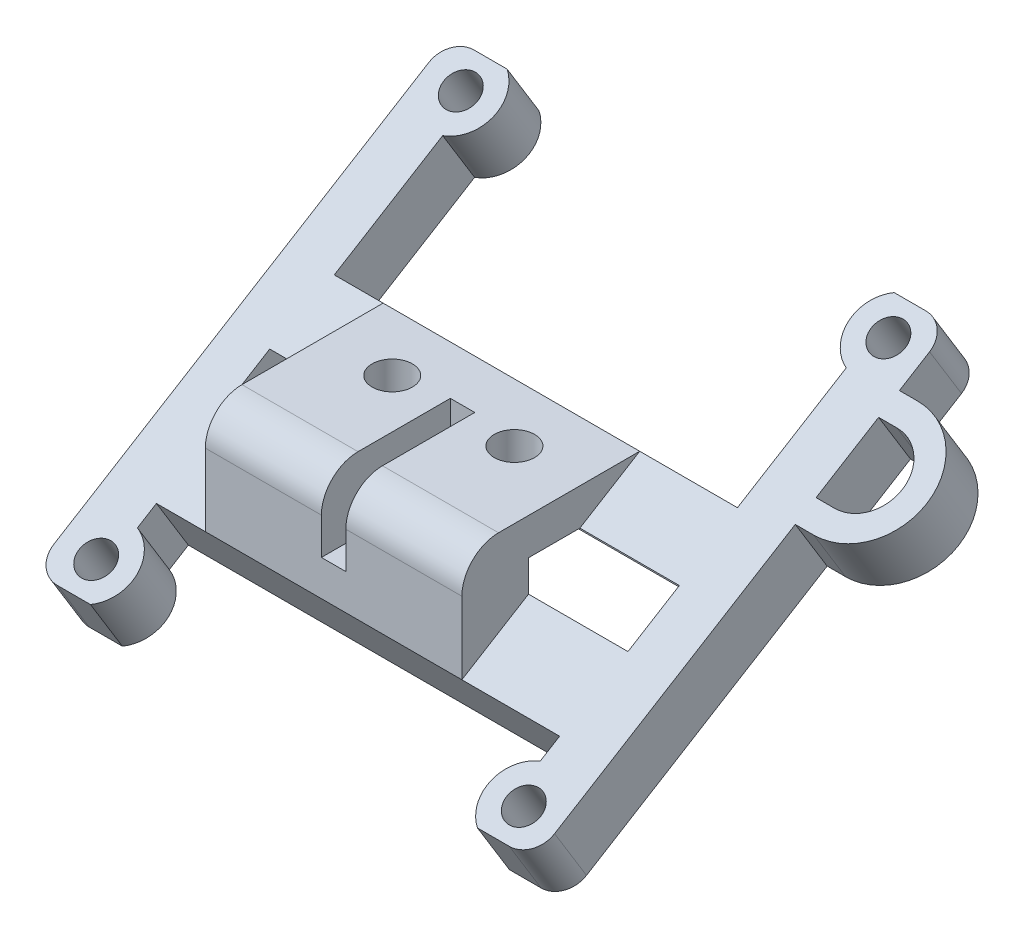
SolidWorks part; units mm, degrees
ref_plane "前视基准面" through (0, 0, 0) normal (0, 0, 1) x (1, 0, 0)
ref_plane "上视基准面" through (0, 0, 0) normal (0, 1, 0) x (1, 0, 0)
ref_plane "右视基准面" through (0, 0, 0) normal (1, 0, 0) x (0, 0, -1)
sketch "草图1" plane through (0, 0, 0) normal (0, 1, 0) x (1, 0, 0)
  line L1 (0, 0) -> (28, 0)
  line L2 (0, 0) -> (0, 15)
  line L3 (0, 15) -> (28, 15)
  line L4 (28, 0) -> (28, 15)
  dimension "D1" = 15
  dimension "D2" = 28
extrude "凸台-拉伸1" add sketch "草图1" along normal blind 5
sketch "草图2" plane through (0, 0, 0) normal (-1, 0, 0) x (0, 0, 1)
  line L0 (4.8114, -9.8007) -> (-29.2942, 11.0992)
  line L1 (-29.2942, 11.0992) -> (-27.988, 13.2308)
  line L2 (4.8114, -9.8007) -> (6.1176, -7.6691)
  line L3 (-27.988, 13.2308) -> (-14.5565, 5)
  line L4 (0, 0) -> (0, -3.9202)
  line L5 (-15, 0) -> (0, 0) construction
  line L6 (0, 5) -> (0, 0) construction
  line L8 (0, -3.9202) -> (6.1176, -7.6691)
  line L9 (0, 0) -> (0, 5)
  line L10 (0, 5) -> (-14.5565, 5)
  dimension "D1" = 2.5
  dimension "D2" = 2.5
extrude "凸台-拉伸2" add sketch "草图2" along normal blind 13 and the other way up to surface other way up to face at (28, 2.5, -7.5)
sketch "草图3" plane through (-13, 0, 0) normal (-1, 0, 0) x (0, 0, 1)
  line L3 (-15, 0) -> (-11.1819, 0)
  line L4 (-11.1819, 0) -> (-15, 2.3397)
  line L5 (-15, 2.3397) -> (-15, 0)
  line L6 (-15, 0) -> (-11.1819, 0)
  line L7 (-11.1819, 0) -> (-15, 2.3397)
  line L8 (-15, 2.3397) -> (-15, 0)
  dimension "D1" = 0
extrude "切除-拉伸1" cut sketch "草图3" against normal through all
sketch "草图8" plane through (0, -4.9816, -3.0527) normal (0, -0.8526, -0.5225) x (1, 0, 0)
  line L4 (28, 9.2233) -> (-13, 9.2233)
  line L5 (-13, 9.2233) -> (-13, -30.7767)
  line L6 (-13, -30.7767) -> (28, -30.7767)
  line L7 (28, -30.7767) -> (28, 9.2233)
  line L8 (28, 9.2233) -> (-13, 9.2233)
  line L9 (-13, 9.2233) -> (-13, -30.7767)
  line L10 (-13, -30.7767) -> (28, -30.7767)
  line L11 (28, -30.7767) -> (28, 9.2233)
  dimension "D1" = 0
extrude "凸台-拉伸3" add sketch "草图8" along normal blind 2.5
sketch "草图4" plane through (0, -7.1132, -4.359) normal (0, -0.8526, -0.5225) x (1, 0, 0)
  circle A0 centre (-9.9452, 6.7233) radius 1.4
  circle A1 centre (25.0548, 6.7233) radius 1.4
  circle A2 centre (25.0548, -28.2767) radius 1.4
  circle A3 centre (-9.9452, -28.2767) radius 1.4
  dimension "D1" = 2.8
  dimension "D2" = 2.8
  dimension "D3" = 2.8
  dimension "D4" = 2.8
extrude "切除-拉伸2" cut sketch "草图4" against normal blind 7
sketch "草图5" plane through (0, 5, 0) normal (0, 1, 0) x (1, 0, 0)
  line L0 (0.5, 9.8) -> (10.5, 9.8) construction
  line L1 (-13, -3.5052) -> (-13, 30.6005) construction
  circle A0 centre (10.5, 9.8) radius 1.65
  circle A1 centre (0.5, 9.8) radius 1.65
  dimension "D1" = 3.3
  dimension "D2" = 3.3
  dimension "D3" = 13.5
  dimension "D4" = 10
extrude "切除-拉伸3" cut sketch "草图5" against normal through all
ref_plane "基准面1" through (0, 2, 0) normal (0, 1, 0) x (1, 0, 0)
sketch "草图6" plane through (0, 2, 0) normal (0, 1, 0) x (1, 0, 0)
  line L1 (-9.391, 13.2275) -> (24.1407, 13.2275)
  line L2 (-9.391, 13.2275) -> (-9.391, 5.454)
  line L3 (-9.391, 5.454) -> (24.1407, 5.454)
  line L4 (24.1407, 13.2275) -> (24.1407, 5.454)
  circle A0 centre (0.5, 9.8) radius 3.1 construction
  circle A1 centre (10.5, 9.8) radius 3.1 construction
  dimension "D1" = 6.2
  dimension "D2" = 6.2
extrude "切除-拉伸4" cut sketch "草图6" against normal blind 11
fillet "圆角1" radius 2 4 edges at (-13, -9.8007, 4.8114) (28, -9.8007, 4.8114) (28, 11.0992, -29.2942) (-13, 11.0992, -29.2942)
sketch "草图9" plane through (0, -2.85, -1.7465) normal (0, 0.8526, 0.5225) x (1, 0, 0)
  line L3 (28, -2.0483) -> (-13, -2.0483) construction
  line L4 (26, -9.2233) -> (-11, -9.2233) construction
  line L5 (-8.2869, -9.2233) -> (23.3965, -9.2233)
  line L6 (-9, -3.8761) -> (-9, -2.0483)
  line L7 (-9, -2.0483) -> (24, -2.0483)
  line L8 (-9, 19.0239) -> (-9, 15.0239)
  line L9 (28, 15.0239) -> (-13, 15.0239) construction
  line L10 (-9, 15.0239) -> (24, 15.0239)
  line L11 (24, 15.0239) -> (24, 19.0239)
  line L12 (-11, 30.7767) -> (26, 30.7767) construction
  line L16 (24, 19.0239) -> (24, 25.4683)
  line L17 (23.3965, 30.7767) -> (-8.2869, 30.7767)
  line L18 (-9, 25.4295) -> (-9, 19.0239)
  line L19 (24, -3.9148) -> (24, -2.0483)
  arc A0 (23.3965, 30.7767) -> (24, 25.4683) centre (25.0548, 28.2767) ccw
  arc A1 (-9, 25.4295) -> (-8.2869, 30.7767) centre (-9.9452, 28.2767) ccw
  arc A4 (-8.2869, -9.2233) -> (-9, -3.8761) centre (-9.9452, -6.7233) ccw
  arc A5 (24, -3.9148) -> (23.3965, -9.2233) centre (25.0548, -6.7233) ccw
  dimension "D2" = 6
  dimension "D3" = 6
  dimension "D4" = 6
  dimension "D5" = 6
extrude "切除-拉伸5" cut sketch "草图9" against normal through all
sketch "草图10" plane through (0, 5, 0) normal (0, 1, 0) x (1, 0, 0)
  line L0 (19.9278, 10.5565) -> (19.9278, -1) construction
  line L2 (6.5011, 10.5565) -> (6.5011, -1)
  line L4 (4.5011, 10.5565) -> (4.5011, -1)
  line L5 (0.0722, 10.5565) -> (0.0722, -1) construction
  line L6 (6.5011, 10.5565) -> (4.5011, 10.5565)
  line L7 (0.0722, 10.5565) -> (-9, 10.5565) construction
  line L8 (4.5011, -1) -> (6.5011, -1)
  line L9 (19.9278, -1) -> (24, -1) construction
  line L10 (19.9278, -1) -> (6.5011, -1) construction
  line L11 (4.5011, -1) -> (0.0722, -1) construction
  line L12 (-13, 0) -> (28, 0) construction
  line L13 (19.9278, 10.5565) -> (6.5011, 10.5565) construction
  line L14 (4.5011, 10.5565) -> (0.0722, 10.5565) construction
  line L15 (-9, 14.5565) -> (24, 14.5565) construction
  line L16 (24, -1) -> (24, 10.5565) construction
  line L17 (24, 10.5565) -> (19.9278, 10.5565) construction
  line L18 (-9, 10.5565) -> (-9, -1) construction
  line L19 (-9, -1) -> (0.0722, -1) construction
  dimension "D2" = 4
  dimension "D3" = 2
  dimension "D1" = 1
extrude "切除-拉伸6" cut sketch "草图10" against normal blind 6
sketch "草图11" plane through (-13, 0, 0) normal (-1, 0, 0) x (0, 0, 1)
  line L0 (0, -3.9202) -> (-14.5565, 5)
  line L1 (4.4124, -6.6241) -> (0, -3.9202) construction
  line L2 (0, 5) -> (-14.5565, 5) construction
  line L3 (-14.5565, 5) -> (-26.2827, 12.1858) construction
  line L4 (-14.5565, 5) -> (0, 5)
  line L5 (0, -3.9202) -> (0, 5) construction
  line L6 (0, 5) -> (0, -3.9202)
extrude "切除-拉伸8" cut sketch "草图11" against normal blind 8
sketch "草图12" plane through (28, 0, 0) normal (1, 0, 0) x (0, 0, -1)
  line L0 (14.5565, 5) -> (0, -3.9202)
  line L1 (0, -3.9202) -> (0, 5)
  line L2 (0, 5) -> (14.5565, 5)
extrude "切除-拉伸9" cut sketch "草图12" against normal blind 12
fillet "圆角2" radius 3 2 edges at (11.2505, 5, 0) (-0.2495, 5, 0)
sketch "草图13" plane through (0, -7.1132, -4.359) normal (0, -0.8526, -0.5225) x (1, 0, 0)
  line L0 (24.8936, -20.8821) -> (29.5126, -20.8821) construction
  line L1 (27.2031, -17.8821) -> (29.5126, -17.8821)
  line L2 (27.2031, -23.8821) -> (29.5126, -23.8821)
  line L3 (27.2031, -15.8821) -> (29.5126, -15.8821)
  line L4 (27.2031, -25.8821) -> (29.5126, -25.8821)
  line L5 (27.2031, -15.8821) -> (27.2031, -17.8821)
  line L6 (27.2031, -23.8821) -> (27.2031, -25.8821)
  line L7 (24.8936, -25.8821) -> (29.5126, -25.8821) construction
  line L8 (24.8936, -23.8821) -> (29.5126, -23.8821) construction
  line L10 (24.8936, -17.8821) -> (29.5126, -17.8821) construction
  line L11 (24.8936, -15.8821) -> (29.5126, -15.8821) construction
  arc A1 (29.5126, -23.8821) -> (29.5126, -17.8821) centre (29.5126, -20.8821) ccw
  arc A2 (29.5126, -25.8821) -> (29.5126, -15.8821) centre (29.5126, -20.8821) ccw
  arc A4 (24.8936, -17.8821) -> (24.8936, -23.8821) centre (24.8936, -20.8821) ccw construction
  arc A5 (24.8936, -15.8821) -> (24.8936, -25.8821) centre (24.8936, -20.8821) ccw construction
  point P2 (27.2031, -20.8821)
  dimension "D1" = 3
  dimension "D2" = 2
extrude "凸台-拉伸4" add sketch "草图13" against normal up to surface (5 mm away) up to face at (22.5409, 1.7031, -9.1765)
